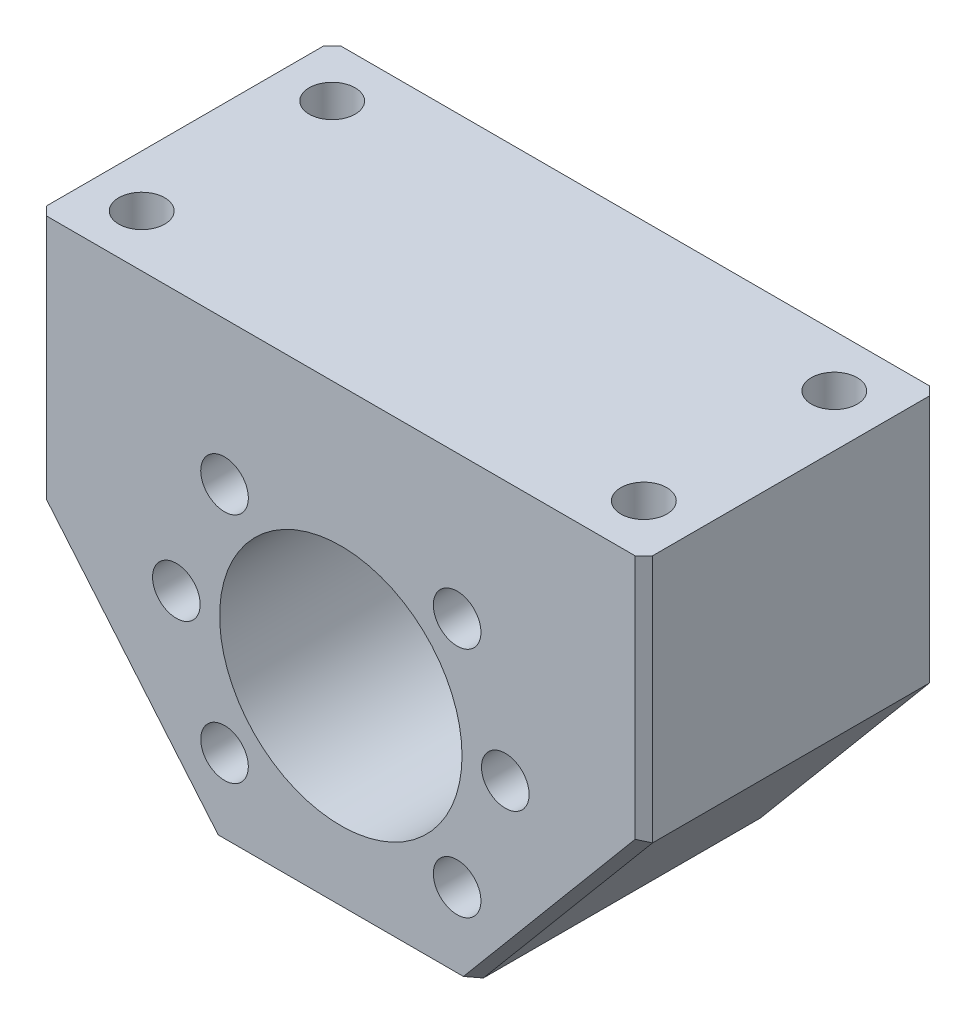
SolidWorks part; units mm, degrees
ref_plane "Front Plane" through (0, 0, 0) normal (0, 0, 1) x (1, 0, 0)
ref_plane "Top Plane" through (0, 0, 0) normal (0, 1, 0) x (1, 0, 0)
ref_plane "Right Plane" through (0, 0, 0) normal (1, 0, 0) x (0, 0, -1)
sketch "Sketch1" plane through (0, 0, 0) normal (0, 0, 1) x (1, 0, 0)
  line L0 (0, 0) -> (0, -22) construction
  line L1 (15.4668, -22) -> (-15.4668, -22)
  line L2 (-15.4668, -22) -> (-35, 1.2788)
  line L3 (-35, 1.2788) -> (-35, 30)
  line L4 (-35, 30) -> (35, 30)
  line L5 (35, 1.2788) -> (35, 30)
  line L6 (15.4668, -22) -> (35, 1.2788)
  line L7 (-19, 0) -> (19, 0) construction
  line L8 (-13.435, -13.435) -> (0, 0) construction
  line L9 (-13.435, 13.435) -> (0, 0) construction
  line L10 (13.435, 13.435) -> (0, 0) construction
  line L11 (13.435, -13.435) -> (0, 0) construction
  circle A0 centre (0, 0) radius 14
  circle A1 centre (0, 0) radius 19 construction
  circle A2 centre (-13.435, -13.435) radius 2.75
  circle A4 centre (-19, 0) radius 2.75
  circle A5 centre (-13.435, 13.435) radius 2.75
  circle A6 centre (13.435, 13.435) radius 2.75
  circle A7 centre (19, 0) radius 2.75
  circle A8 centre (13.435, -13.435) radius 2.75
  point P9 (0, 30)
  dimension "D1" = 28
  dimension "D2" = 30
  dimension "D3" = 22
  dimension "D5" = 5.5
  dimension "D7" = 5.5
  dimension "D9" = 38
  dimension "D4" = 130
  dimension "D6" = 45
  dimension "D8" = 70
extrude "Boss-Extrude1" add sketch "Sketch1" along normal mid plane 34
sketch "Sketch2" plane through (0, 30, 0) normal (0, 1, 0) x (1, 0, 0)
  line L1 (29, -11) -> (-29, -11) construction
  line L2 (29, -11) -> (29, 11) construction
  line L3 (29, 11) -> (-29, 11) construction
  line L4 (-29, -11) -> (-29, 11) construction
  line L5 (29, -11) -> (-29, 11) construction
  line L6 (29, 11) -> (-29, -11) construction
  circle A0 centre (-29, 11) radius 2.65
  circle A1 centre (-29, -11) radius 2.65
  circle A2 centre (29, -11) radius 2.65
  circle A3 centre (29, 11) radius 2.65
  point P0 (0, 0)
  dimension "D1" = 5.3
  dimension "D2" = 22
  dimension "D3" = 58
extrude "Cut-Extrude1" cut sketch "Sketch2" against normal blind 10
chamfer "Chamfer1" distance 1 angle 45 9 edges at (-15.4668, -22, 0) (-25.2334, -10.3606, -17) (-35, 15.6394, -17) (-35, 15.6394, 17) (-25.2334, -10.3606, 17) (25.2334, -10.3606, 17) (35, 15.6394, 17) (35, 15.6394, -17) (25.2334, -10.3606, -17)
